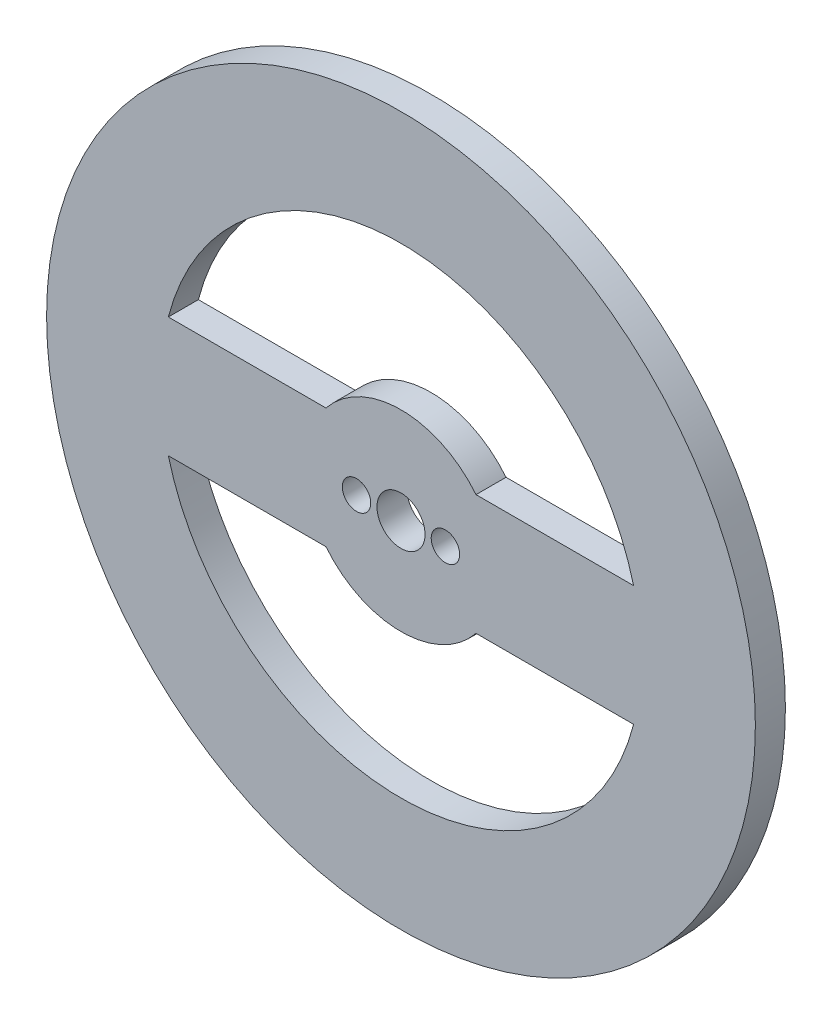
SolidWorks part; units mm, degrees
ref_plane "Front Plane" through (0, 0, 0) normal (0, 0, 1) x (1, 0, 0)
ref_plane "Top Plane" through (0, 0, 0) normal (0, 1, 0) x (1, 0, 0)
ref_plane "Right Plane" through (0, 0, 0) normal (1, 0, 0) x (0, 0, -1)
sketch "Sketch1" plane through (0, 0, 0) normal (0, 0, 1) x (1, 0, 0)
  circle A0 centre (0, 0) radius 37.465
  dimension "D1" = 74.93
extrude "Boss-Extrude1" add sketch "Sketch1" along normal blind 3.175
sketch "Sketch2" plane through (0, 0, 3.175) normal (0, 0, 1) x (1, 0, 0)
  line L0 (-24.5934, -6.35) -> (-7.9311, -6.35)
  line L1 (7.9311, 6.35) -> (24.5934, 6.35)
  line L2 (7.9311, -6.35) -> (24.5934, -6.35)
  line L3 (-24.5934, 6.35) -> (-7.9311, 6.35)
  line L4 (-24.5934, -6.35) -> (24.5934, 6.35) construction
  line L5 (24.5934, -6.35) -> (-24.5934, 6.35) construction
  arc A0 (7.9311, 6.35) -> (-7.9311, 6.35) centre (0, 0) ccw
  arc A1 (-24.5934, -6.35) -> (24.5934, -6.35) centre (0, 0) ccw
  arc A2 (24.5934, 6.35) -> (-24.5934, 6.35) centre (0, 0) ccw
  arc A3 (-7.9311, -6.35) -> (7.9311, -6.35) centre (0, 0) ccw
  dimension "D1" = 20.32
  dimension "D2" = 50.8
  dimension "D3" = 12.7
extrude "Cut-Extrude1" cut sketch "Sketch2" against normal through all
sketch "Sketch3" plane through (0, 0, 3.175) normal (0, 0, 1) x (1, 0, 0)
  circle A0 centre (0, 0) radius 2.54
  dimension "D1" = 5.08
extrude "Cut-Extrude2" cut sketch "Sketch3" against normal through all
sketch "Sketch4" plane through (0, 0, 0) normal (0, 0, -1) x (-1, 0, 0)
  line L0 (-37.465, 0) -> (37.465, 0) construction
  circle A0 centre (-4.699, 0) radius 1.505
  circle A1 centre (4.699, 0) radius 1.505
  circle A3 centre (0, 0) radius 2.54 construction
  circle A4 centre (0, 0) radius 37.465 construction
  dimension "D1" = 3.01
  dimension "D2" = 3.01
  dimension "D3" = 4.699
  dimension "D4" = 4.699
extrude "Cut-Extrude3" cut sketch "Sketch4" against normal through all
